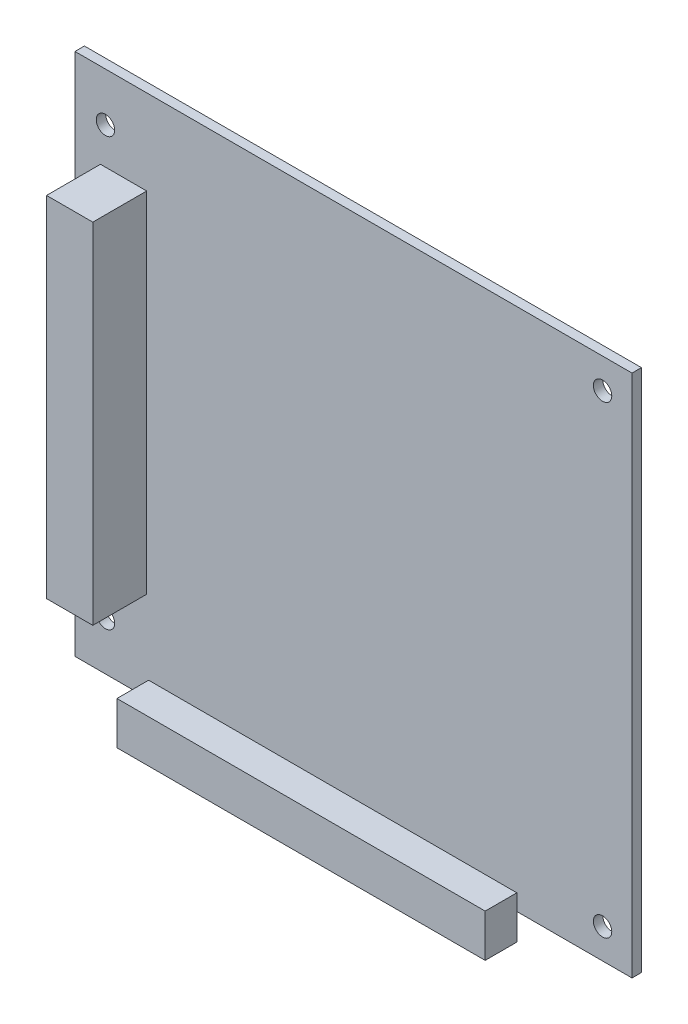
SolidWorks part; units mm, degrees
ref_plane "Front Plane" through (0, 0, 0) normal (0, 0, 1) x (1, 0, 0)
ref_plane "Top Plane" through (0, 0, 0) normal (0, 1, 0) x (1, 0, 0)
ref_plane "Right Plane" through (0, 0, 0) normal (1, 0, 0) x (0, 0, -1)
sketch "Sketch1" plane through (0, 0, 0) normal (0, 0, 1) x (1, 0, 0)
  line L1 (-48.0314, -45.1739) -> (48.0314, -45.1739)
  line L2 (-48.0314, -45.1739) -> (-48.0314, 45.1739)
  line L3 (-48.0314, 45.1739) -> (48.0314, 45.1739)
  line L4 (48.0314, -45.1739) -> (48.0314, 45.1739)
  line L5 (-48.0314, -45.1739) -> (48.0314, 45.1739) construction
  line L6 (-48.0314, 45.1739) -> (48.0314, -45.1739) construction
  point P0 (0, 0)
  dimension "D1" = 96.0628
  dimension "D2" = 90.3478
extrude "PCB" add sketch "Sketch1" along normal blind 1.6256
sketch "Sketch5" plane through (0, 0, 1.6256) normal (0, 0, 1) x (1, 0, 0)
  line L0 (-42.7736, 45.1739) -> (-42.7736, 36.83) construction
  line L1 (48.0314, 45.1739) -> (-48.0314, 45.1739) construction
  line L2 (-42.7736, 36.83) -> (-42.7736, -36.83) construction
  line L3 (-42.7736, -36.83) -> (-42.7736, -45.1739) construction
  line L4 (-48.0314, -45.1739) -> (48.0314, -45.1739) construction
  line L5 (48.0314, -45.1739) -> (48.0314, 45.1739) construction
  line L6 (42.9514, 45.1739) -> (42.9514, 40.005) construction
  line L7 (42.9514, 40.005) -> (42.9514, -40.005) construction
  line L8 (42.9514, -40.005) -> (42.9514, -45.1739) construction
  circle A0 centre (-42.7736, 36.83) radius 1.5875
  circle A1 centre (42.9514, 40.005) radius 1.5875
  circle A2 centre (42.9514, -40.005) radius 1.5875
  circle A3 centre (-42.7736, -36.83) radius 1.5875
  dimension "D5" = 3.175
  dimension "D1" = 73.66
  dimension "D2" = 90.805
  dimension "D3" = 80.01
  dimension "D4" = 5.08
extrude "PCB_Holes" cut sketch "Sketch5" against normal through all
sketch "Sketch2" plane through (0, 0, 1.6256) normal (0, 0, 1) x (1, 0, 0)
  line L0 (-48.0314, 45.1739) -> (-48.0314, -45.1739) construction
  line L1 (-43.6372, 30.5181) -> (-35.6616, 30.5181)
  line L2 (-43.6372, 30.5181) -> (-43.6372, -29.7053)
  line L3 (-43.6372, -29.7053) -> (-35.6616, -29.7053)
  line L4 (-35.6616, 30.5181) -> (-35.6616, -29.7053)
  line L5 (-48.0314, -45.1739) -> (48.0314, -45.1739) construction
  dimension "D1" = 60.2234
  dimension "D2" = 7.9756
  dimension "D3" = 4.3942
  dimension "D4" = 15.4686
extrude "PCI-104_Connector" add sketch "Sketch2" along normal blind 9.2964
sketch "Sketch6" plane through (0, 0, 1.6256) normal (0, 0, 1) x (1, 0, 0)
  line L0 (-48.0314, -45.1739) -> (48.0314, -45.1739) construction
  line L1 (-35.3314, -42.3799) -> (28.1686, -42.3799)
  line L2 (-35.3314, -42.3799) -> (-35.3314, -49.7459)
  line L3 (-35.3314, -49.7459) -> (28.1686, -49.7459)
  line L4 (28.1686, -42.3799) -> (28.1686, -49.7459)
  line L5 (-48.0314, 45.1739) -> (-48.0314, -45.1739) construction
  dimension "D1" = 7.366
  dimension "D2" = 4.572
  dimension "D3" = 63.5
  dimension "D4" = 12.7
extrude "PCB_Edge_Conns" add sketch "Sketch6" along normal blind 5.461
